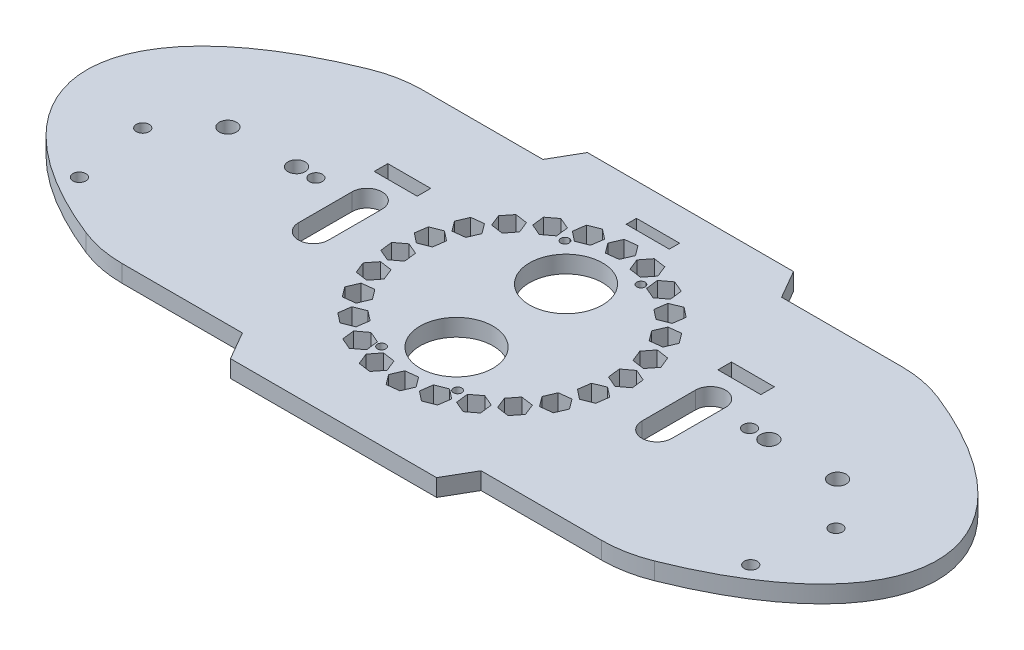
SolidWorks part; units mm, degrees
ref_plane "Front Plane" through (0, 0, 0) normal (0, 0, 1) x (1, 0, 0)
ref_plane "Top Plane" through (0, 0, 0) normal (0, 1, 0) x (1, 0, 0)
ref_plane "Right Plane" through (0, 0, 0) normal (1, 0, 0) x (0, 0, -1)
sketch "Sketch2" plane through (0, 0, 0) normal (0, 1, 0) x (1, 0, 0)
  line L0 (35.0207, 12.9363) -> (45.0255, 12.9363)
  line L1 (-35.0207, 16.0905) -> (-45.0255, 16.0905)
  line L2 (-35.0207, 16.0905) -> (-35.0207, 12.9363)
  line L5 (-35.0207, 12.9363) -> (-45.0255, 12.9363)
  line L158 (-45.0255, 16.0905) -> (-45.0255, 12.9363)
  line L159 (45.0255, 16.0905) -> (45.0255, 12.9363)
  line L160 (35.0207, 16.0905) -> (45.0255, 16.0905)
  line L163 (35.0207, 16.0905) -> (35.0207, 12.9363)
  line L170 (53, 6.8264) -> (53, 2.8264) construction
  line L171 (-53, 2.8264) -> (-53, 6.8264) construction
  line L172 (0, 0) -> (0, 77.4977) construction
  line L173 (0, 0) -> (-78.1193, 0) construction
  line L174 (258.2537, 0) -> (-149, 0) construction
  line L175 (-27.7927, -35) -> (-55.7927, -35)
  line L176 (-27.7927, 35) -> (-55.7927, 35)
  line L177 (-55.7927, 7) -> (-55.7927, -7) construction
  line L178 (27.7927, -35) -> (55.7927, -35)
  line L179 (-24, 41.5692) -> (-27.7927, 35)
  line L180 (-27.7927, -35) -> (-24, -41.5692)
  line L181 (-24, -41.5692) -> (24, -41.5692)
  line L182 (24, -41.5692) -> (27.7927, -35)
  line L183 (27.7927, 35) -> (24, 41.5692)
  line L184 (24, 41.5692) -> (-24, 41.5692)
  line L185 (27.7927, 35) -> (55.7927, 35)
  line L186 (-9.4773, 26.7992) -> (-9.8869, 23.9416)
  line L187 (-13.0924, 19.4317) -> (-10.7822, 21.1627)
  line L188 (-10.7822, 21.1627) -> (-11.1261, 24.0288)
  line L189 (-11.1261, 24.0288) -> (-13.7803, 25.1641)
  line L190 (-13.7803, 25.1641) -> (-16.0905, 23.4331)
  line L191 (-16.0905, 23.4331) -> (-15.7466, 20.5669)
  line L192 (-15.7466, 20.5669) -> (-13.0924, 19.4317)
  line L193 (-9.8869, 23.9416) -> (-7.617, 22.1581)
  line L194 (-7.617, 22.1581) -> (-4.9375, 23.2322)
  line L195 (-4.9375, 23.2322) -> (-4.5279, 26.0897)
  line L196 (-4.5279, 26.0897) -> (-6.7978, 27.8732)
  line L197 (-6.7978, 27.8732) -> (-9.4773, 26.7992)
  line L198 (-2.2182, 28.3389) -> (-3.3535, 25.6848)
  line L199 (-3.3535, 25.6848) -> (-1.6225, 23.3745)
  line L200 (-1.6225, 23.3745) -> (1.2437, 23.7185)
  line L201 (1.2437, 23.7185) -> (2.3789, 26.3726)
  line L202 (2.3789, 26.3726) -> (0.648, 28.6829)
  line L203 (0.648, 28.6829) -> (-2.2182, 28.3389)
  line L204 (5.192, 27.9474) -> (3.4085, 25.6775)
  line L205 (3.4085, 25.6775) -> (4.4826, 22.998)
  line L206 (4.4826, 22.998) -> (7.3401, 22.5884)
  line L207 (7.3401, 22.5884) -> (9.1236, 24.8583)
  line L208 (9.1236, 24.8583) -> (8.0496, 27.5378)
  line L209 (8.0496, 27.5378) -> (5.192, 27.9474)
  line L210 (12.2484, 25.6513) -> (9.9382, 23.9204)
  line L211 (9.9382, 23.9204) -> (10.2821, 21.0542)
  line L212 (10.2821, 21.0542) -> (12.9363, 19.919)
  line L213 (12.9363, 19.919) -> (15.2465, 21.6499)
  line L214 (15.2465, 21.6499) -> (14.9026, 24.5161)
  line L215 (14.9026, 24.5161) -> (12.2484, 25.6513)
  line L216 (18.4701, 21.6072) -> (15.7906, 20.5331)
  line L217 (15.7906, 20.5331) -> (15.381, 17.6756)
  line L218 (15.381, 17.6756) -> (17.6509, 15.8921)
  line L219 (17.6509, 15.8921) -> (20.3304, 16.9661)
  line L220 (20.3304, 16.9661) -> (20.74, 19.8237)
  line L221 (20.74, 19.8237) -> (18.4701, 21.6072)
  line L222 (23.4331, 16.0905) -> (20.5669, 15.7466)
  line L223 (20.5669, 15.7466) -> (19.4317, 13.0924)
  line L224 (19.4317, 13.0924) -> (21.1627, 10.7822)
  line L225 (21.1627, 10.7822) -> (24.0288, 11.1261)
  line L226 (24.0288, 11.1261) -> (25.1641, 13.7803)
  line L227 (25.1641, 13.7803) -> (23.4331, 16.0905)
  line L228 (26.7992, 9.4773) -> (23.9416, 9.8869)
  line L229 (23.9416, 9.8869) -> (22.1581, 7.617)
  line L230 (22.1581, 7.617) -> (23.2322, 4.9375)
  line L231 (23.2322, 4.9375) -> (26.0897, 4.5279)
  line L232 (26.0897, 4.5279) -> (27.8732, 6.7978)
  line L233 (27.8732, 6.7978) -> (26.7992, 9.4773)
  line L234 (28.3389, 2.2182) -> (25.6848, 3.3535)
  line L235 (25.6848, 3.3535) -> (23.3745, 1.6225)
  line L236 (23.3745, 1.6225) -> (23.7185, -1.2437)
  line L237 (23.7185, -1.2437) -> (26.3726, -2.3789)
  line L238 (26.3726, -2.3789) -> (28.6829, -0.648)
  line L239 (28.6829, -0.648) -> (28.3389, 2.2182)
  line L240 (27.9474, -5.192) -> (25.6775, -3.4085)
  line L241 (25.6775, -3.4085) -> (22.998, -4.4826)
  line L242 (22.998, -4.4826) -> (22.5884, -7.3401)
  line L243 (22.5884, -7.3401) -> (24.8583, -9.1236)
  line L244 (24.8583, -9.1236) -> (27.5378, -8.0496)
  line L245 (27.5378, -8.0496) -> (27.9474, -5.192)
  line L246 (25.6513, -12.2484) -> (23.9204, -9.9382)
  line L247 (23.9204, -9.9382) -> (21.0542, -10.2821)
  line L248 (21.0542, -10.2821) -> (19.919, -12.9363)
  line L249 (19.919, -12.9363) -> (21.6499, -15.2465)
  line L250 (21.6499, -15.2465) -> (24.5161, -14.9026)
  line L251 (24.5161, -14.9026) -> (25.6513, -12.2484)
  line L252 (21.6072, -18.4701) -> (20.5331, -15.7906)
  line L253 (20.5331, -15.7906) -> (17.6756, -15.381)
  line L254 (17.6756, -15.381) -> (15.8921, -17.6509)
  line L255 (15.8921, -17.6509) -> (16.9661, -20.3304)
  line L256 (16.9661, -20.3304) -> (19.8237, -20.74)
  line L257 (19.8237, -20.74) -> (21.6072, -18.4701)
  line L258 (16.0905, -23.4331) -> (15.7466, -20.5669)
  line L259 (15.7466, -20.5669) -> (13.0924, -19.4317)
  line L260 (13.0924, -19.4317) -> (10.7822, -21.1627)
  line L261 (10.7822, -21.1627) -> (11.1261, -24.0288)
  line L262 (11.1261, -24.0288) -> (13.7803, -25.1641)
  line L263 (13.7803, -25.1641) -> (16.0905, -23.4331)
  line L264 (9.4773, -26.7992) -> (9.8869, -23.9416)
  line L265 (9.8869, -23.9416) -> (7.617, -22.1581)
  line L266 (7.617, -22.1581) -> (4.9375, -23.2322)
  line L267 (4.9375, -23.2322) -> (4.5279, -26.0897)
  line L268 (4.5279, -26.0897) -> (6.7978, -27.8732)
  line L269 (6.7978, -27.8732) -> (9.4773, -26.7992)
  line L270 (2.2182, -28.3389) -> (3.3535, -25.6848)
  line L271 (3.3535, -25.6848) -> (1.6225, -23.3745)
  line L272 (1.6225, -23.3745) -> (-1.2437, -23.7185)
  line L273 (-1.2437, -23.7185) -> (-2.3789, -26.3726)
  line L274 (-2.3789, -26.3726) -> (-0.648, -28.6829)
  line L275 (-0.648, -28.6829) -> (2.2182, -28.3389)
  line L276 (-5.192, -27.9474) -> (-3.4085, -25.6775)
  line L277 (-3.4085, -25.6775) -> (-4.4826, -22.998)
  line L278 (-4.4826, -22.998) -> (-7.3401, -22.5884)
  line L279 (-7.3401, -22.5884) -> (-9.1236, -24.8583)
  line L280 (-9.1236, -24.8583) -> (-8.0496, -27.5378)
  line L281 (-8.0496, -27.5378) -> (-5.192, -27.9474)
  line L282 (-12.2484, -25.6513) -> (-9.9382, -23.9204)
  line L283 (-9.9382, -23.9204) -> (-10.2821, -21.0542)
  line L284 (-10.2821, -21.0542) -> (-12.9363, -19.919)
  line L285 (-12.9363, -19.919) -> (-15.2465, -21.6499)
  line L286 (-15.2465, -21.6499) -> (-14.9026, -24.5161)
  line L287 (-14.9026, -24.5161) -> (-12.2484, -25.6513)
  line L288 (-18.4701, -21.6072) -> (-15.7906, -20.5331)
  line L289 (-15.7906, -20.5331) -> (-15.381, -17.6756)
  line L290 (-15.381, -17.6756) -> (-17.6509, -15.8921)
  line L291 (-17.6509, -15.8921) -> (-20.3304, -16.9661)
  line L292 (-20.3304, -16.9661) -> (-20.74, -19.8237)
  line L293 (-20.74, -19.8237) -> (-18.4701, -21.6072)
  line L294 (-23.4331, -16.0905) -> (-20.5669, -15.7466)
  line L295 (-20.5669, -15.7466) -> (-19.4317, -13.0924)
  line L296 (-19.4317, -13.0924) -> (-21.1627, -10.7822)
  line L297 (-21.1627, -10.7822) -> (-24.0288, -11.1261)
  line L298 (-24.0288, -11.1261) -> (-25.1641, -13.7803)
  line L299 (-25.1641, -13.7803) -> (-23.4331, -16.0905)
  line L300 (-26.7992, -9.4773) -> (-23.9416, -9.8869)
  line L301 (-23.9416, -9.8869) -> (-22.1581, -7.617)
  line L302 (-22.1581, -7.617) -> (-23.2322, -4.9375)
  line L303 (-23.2322, -4.9375) -> (-26.0897, -4.5279)
  line L304 (-26.0897, -4.5279) -> (-27.8732, -6.7978)
  line L305 (-27.8732, -6.7978) -> (-26.7992, -9.4773)
  line L306 (-28.3389, -2.2182) -> (-25.6848, -3.3535)
  line L307 (-25.6848, -3.3535) -> (-23.3745, -1.6225)
  line L308 (-23.3745, -1.6225) -> (-23.7185, 1.2437)
  line L309 (-23.7185, 1.2437) -> (-26.3726, 2.3789)
  line L310 (-26.3726, 2.3789) -> (-28.6829, 0.648)
  line L311 (-28.6829, 0.648) -> (-28.3389, -2.2182)
  line L312 (-27.9474, 5.192) -> (-25.6775, 3.4085)
  line L313 (-25.6775, 3.4085) -> (-22.998, 4.4826)
  line L314 (-22.998, 4.4826) -> (-22.5884, 7.3401)
  line L315 (-22.5884, 7.3401) -> (-24.8583, 9.1236)
  line L316 (-24.8583, 9.1236) -> (-27.5378, 8.0496)
  line L317 (-27.5378, 8.0496) -> (-27.9474, 5.192)
  line L318 (-25.6513, 12.2484) -> (-23.9204, 9.9382)
  line L319 (-23.9204, 9.9382) -> (-21.0542, 10.2821)
  line L320 (-21.0542, 10.2821) -> (-19.919, 12.9363)
  line L321 (-19.919, 12.9363) -> (-21.6499, 15.2465)
  line L322 (-21.6499, 15.2465) -> (-24.5161, 14.9026)
  line L323 (-24.5161, 14.9026) -> (-25.6513, 12.2484)
  line L324 (-21.6072, 18.4701) -> (-20.5331, 15.7906)
  line L325 (-20.5331, 15.7906) -> (-17.6756, 15.381)
  line L326 (-17.6756, 15.381) -> (-15.8921, 17.6509)
  line L327 (-15.8921, 17.6509) -> (-16.9661, 20.3304)
  line L328 (-16.9661, 20.3304) -> (-19.8237, 20.74)
  line L329 (-19.8237, 20.74) -> (-21.6072, 18.4701)
  line L330 (-72, -8.711) -> (-72, -26.011) construction
  line L331 (72, -8.711) -> (72, -26.011) construction
  line L332 (-39.9936, -6.2326) -> (-39.9936, 6.2326) construction
  line L333 (-36.4936, -6.2326) -> (-36.4936, 6.2326)
  line L334 (-43.4936, -6.2326) -> (-43.4936, 6.2326)
  line L335 (39.9936, -6.2326) -> (39.9936, 6.2326) construction
  line L336 (36.4936, -6.2326) -> (36.4936, 6.2326)
  line L337 (43.4936, -6.2326) -> (43.4936, 6.2326)
  line L338 (5.0207, 34.0173) -> (-5.0207, 34.0173)
  line L339 (5.0207, 34.0173) -> (5.0207, 31.6174)
  line L340 (5.0207, 31.6174) -> (-5.0207, 31.6174)
  line L341 (-5.0207, 34.0173) -> (-5.0207, 31.6174)
  line L342 (5.0207, 34.0173) -> (-5.0207, 31.6174) construction
  line L343 (5.0207, 31.6174) -> (-5.0207, 34.0173) construction
  arc A47 (-66.1576, 33.011) -> (-55.7927, 35) centre (-55.7927, 7) cw
  arc A48 (-55.7927, -35) -> (-66.1576, -33.011) centre (-55.7927, -7) cw
  circle A49 centre (0, 0) radius 41.5692 construction
  arc A50 (55.7927, -35) -> (66.1576, -33.011) centre (55.7927, -7) ccw
  arc A51 (66.1576, 33.011) -> (55.7927, 35) centre (55.7927, 7) ccw
  circle A52 centre (-78.1869, -22.5836) radius 1.5
  circle A53 centre (-13.4363, 22.2979) radius 2.5 construction
  circle A54 centre (-7.2074, 25.0157) radius 2.5 construction
  circle A55 centre (-0.4873, 26.0287) radius 2.5 construction
  circle A56 centre (6.2661, 25.2679) radius 2.5 construction
  circle A57 centre (12.5924, 22.7851) radius 2.5 construction
  circle A58 centre (18.0605, 18.7496) radius 2.5 construction
  circle A59 centre (22.2979, 13.4363) radius 2.5 construction
  circle A60 centre (25.0157, 7.2074) radius 2.5 construction
  circle A61 centre (26.0287, 0.4873) radius 2.5 construction
  circle A62 centre (25.2679, -6.2661) radius 2.5 construction
  circle A63 centre (22.7851, -12.5924) radius 2.5 construction
  circle A64 centre (18.7496, -18.0605) radius 2.5 construction
  circle A65 centre (13.4363, -22.2979) radius 2.5 construction
  circle A66 centre (7.2074, -25.0157) radius 2.5 construction
  circle A67 centre (0.4873, -26.0287) radius 2.5 construction
  circle A68 centre (-6.2661, -25.2679) radius 2.5 construction
  circle A69 centre (-12.5924, -22.7851) radius 2.5 construction
  circle A70 centre (-18.0605, -18.7496) radius 2.5 construction
  circle A71 centre (-22.2979, -13.4363) radius 2.5 construction
  circle A72 centre (-25.0157, -7.2074) radius 2.5 construction
  circle A73 centre (-26.0287, -0.4873) radius 2.5 construction
  circle A74 centre (-25.2679, 6.2661) radius 2.5 construction
  circle A75 centre (-22.7851, 12.5924) radius 2.5 construction
  circle A76 centre (-18.7496, 18.0605) radius 2.5 construction
  circle A77 centre (-71, 4.8264) radius 2
  circle A78 centre (-55, 4.8264) radius 2
  circle A79 centre (71, 4.8264) radius 2
  circle A80 centre (55, 4.8264) radius 2
  arc A81 (-36.4936, -6.2326) -> (-43.4936, -6.2326) centre (-39.9936, -6.2326) cw
  arc A82 (-43.4936, 6.2326) -> (-36.4936, 6.2326) centre (-39.9936, 6.2326) cw
  arc A83 (36.4936, -6.2326) -> (43.4936, -6.2326) centre (39.9936, -6.2326) ccw
  arc A84 (43.4936, 6.2326) -> (36.4936, 6.2326) centre (39.9936, 6.2326) ccw
  circle A85 centre (-80.7335, -5.2699) radius 1.5
  circle A86 centre (78.1869, -22.5836) radius 1.5
  circle A87 centre (80.7335, -5.2699) radius 1.5
  circle A88 centre (0.0064, 12.5755) radius 8.5
  circle A89 centre (0.0064, -12.9245) radius 8.5
  circle A90 centre (-8.8436, 21.1755) radius 0.975
  circle A91 centre (8.8564, 21.1755) radius 0.975
  circle A92 centre (8.8564, -21.5245) radius 0.975
  circle A93 centre (-8.8436, -21.5245) radius 0.975
  circle A94 centre (-50.5, 4.8264) radius 1.5
  circle A95 centre (50.5, 4.8264) radius 1.5
  conic Q2 (-66.1576, -33.011) -> (-66.1576, 33.011) control (-149, 0) rho 0.396445
  conic Q3 (66.1576, -33.011) -> (66.1576, 33.011) control (149, 0) rho 0.396445
  point P12 (-50.6539, 4.8264)
  point P284 (51.7016, 0)
  point P513 (0, 0)
  point P522 (0, 32.8173)
  point P536 (-39.9936, 0)
  point P543 (39.9936, 0)
  dimension "D5" = 3
  dimension "D6" = 2.5
  dimension "D18" = 28
  dimension "D20" = 5
  dimension "D21" = 4
  dimension "D4" = 3
  dimension "D7" = 2.5
  dimension "D16" = 48
  dimension "D17" = 28
  dimension "D19" = 198
  dimension "D22" = 16
  dimension "D23" = 70
  dimension "D24" = 50
  dimension "D25" = 110
  dimension "D26" = 17.3
  dimension "D27" = 27
  dimension "D28" = 7
  dimension "D29" = 40
  dimension "D30" = 40.7399
extrude "Boss-Extrude1" add sketch "Sketch2" along normal blind 4
